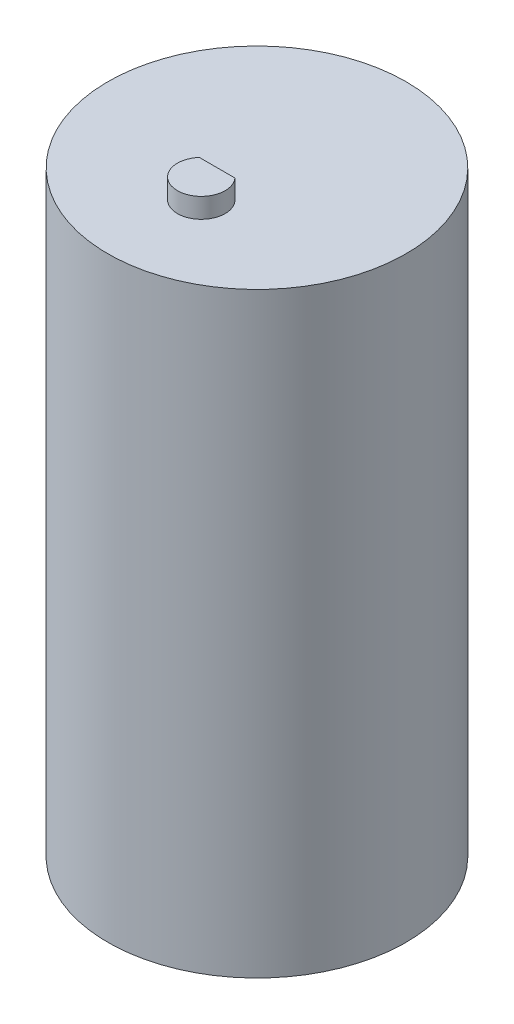
SolidWorks part; units mm, degrees
ref_plane "Front Plane" through (0, 0, 0) normal (0, 0, 1) x (1, 0, 0)
ref_plane "Top Plane" through (0, 0, 0) normal (0, 1, 0) x (1, 0, 0)
ref_plane "Right Plane" through (0, 0, 0) normal (1, 0, 0) x (0, 0, -1)
sketch "Sketch1" plane through (0, 0, 0) normal (0, 1, 0) x (1, 0, 0)
  circle A0 centre (0, 0) radius 19.05
  dimension "D1" = 38.1
extrude "Boss-Extrude1" add sketch "Sketch1" along normal blind 76.2
sketch "Sketch2" plane through (0, 76.2, 0) normal (0, 1, 0) x (1, 0, 0)
  line L0 (0, -4.064) -> (0, -7.112)
  line L1 (0, -5.0817) -> (2.2733, -5.0817)
  line L2 (2.2733, -5.0817) -> (-2.2733, -5.0817)
  circle A0 centre (0, -7.112) radius 3.048
  dimension "D1" = 6.096
  dimension "D2" = 7.112
extrude "Boss-Extrude3" add sketch "Sketch2" along normal blind 2.54
